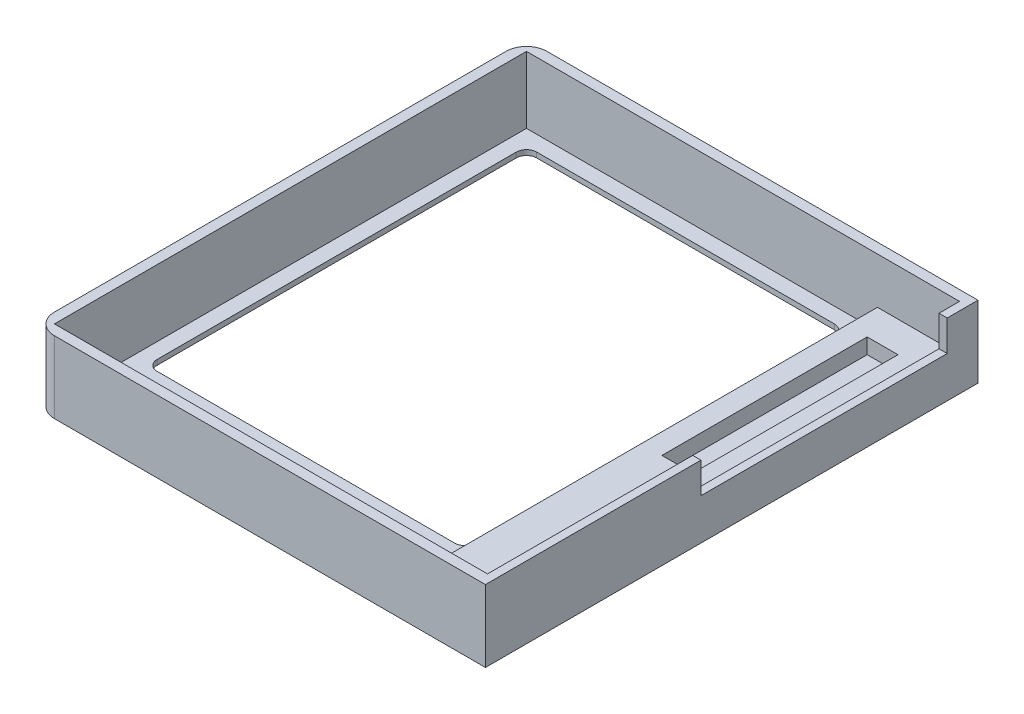
SolidWorks part; units mm, degrees
ref_plane "Front Plane" through (0, 0, 0) normal (0, 0, 1) x (1, 0, 0)
ref_plane "Top Plane" through (0, 0, 0) normal (0, 1, 0) x (1, 0, 0)
ref_plane "Right Plane" through (0, 0, 0) normal (1, 0, 0) x (0, 0, -1)
sketch "Sketch1" plane through (0, 0, 0) normal (0, 1, 0) x (1, 0, 0)
  line L1 (0, 0) -> (44, 0)
  line L2 (0, 0) -> (0, 48)
  line L3 (0, 48) -> (44, 48)
  line L4 (44, 0) -> (44, 48)
  dimension "D1" = 44
  dimension "D2" = 48
extrude "Boss-Extrude1" add sketch "Sketch1" along normal blind 7
sketch "Sketch2" plane through (0, 7, 0) normal (0, 1, 0) x (1, 0, 0)
  line L0 (44, 48) -> (0, 48) construction
  line L1 (1, 47) -> (43.2, 47)
  line L2 (1, 47) -> (1, 1)
  line L3 (1, 1) -> (43.2, 1)
  line L4 (43.2, 47) -> (43.2, 1)
  line L5 (0, 0) -> (44, 0) construction
  line L6 (0, 48) -> (0, 0) construction
  dimension "D1" = 1
  dimension "D2" = 1
  dimension "D3" = 1
  dimension "D4" = 42.2
extrude "Cut-Extrude1" cut sketch "Sketch2" against normal blind 6.5
sketch "Sketch3" plane through (0, 0.5, 0) normal (0, 1, 0) x (1, 0, 0)
  line L0 (1, 47) -> (1, 1) construction
  line L1 (2.5, 45.5) -> (33.5, 45.5)
  line L2 (2.5, 45.5) -> (2.5, 8.5)
  line L3 (2.5, 8.5) -> (33.5, 8.5)
  line L4 (33.5, 45.5) -> (33.5, 8.5)
  line L5 (43.2, 47) -> (1, 47) construction
  line L6 (1, 1) -> (43.2, 1) construction
  dimension "D1" = 1.5
  dimension "D2" = 1.5
  dimension "D3" = 7.5
  dimension "D4" = 31
extrude "Cut-Extrude2" cut sketch "Sketch3" against normal up to next
sketch "Sketch4" plane through (0, 0.5, 0) normal (0, 1, 0) x (1, 0, 0)
  line L0 (43.2, 47) -> (1, 47) construction
  line L1 (35.2, 47) -> (43.2, 47)
  line L2 (35.2, 47) -> (35.2, 1)
  line L3 (35.2, 1) -> (43.2, 1)
  line L4 (43.2, 47) -> (43.2, 1)
  dimension "D1" = 8
extrude "Boss-Extrude2" add sketch "Sketch4" along normal blind 2
sketch "Sketch5" plane through (0, 7, 0) normal (0, 1, 0) x (1, 0, 0)
  line L0 (43.2, 1) -> (43.2, 47) construction
  line L1 (43.2, 45) -> (44, 45)
  line L2 (43.2, 45) -> (43.2, 21)
  line L3 (43.2, 21) -> (44, 21)
  line L4 (44, 45) -> (44, 21)
  line L5 (44, 0) -> (44, 48) construction
  line L6 (43.2, 47) -> (1, 47) construction
  line L7 (35.2, 1) -> (43.2, 1) construction
  dimension "D1" = 2
  dimension "D2" = 20
extrude "Cut-Extrude3" cut sketch "Sketch5" against normal blind 3
fillet "Fillet1" radius 2 2 edges at (0, 3.5, -48) (0, 3.5, 0)
fillet "Fillet2" radius 1 4 edges at (33.5, 0.25, -45.5) (33.5, 0.25, -8.5) (2.5, 0.25, -45.5) (2.5, 0.25, -8.5)
sketch "Sketch6" plane through (0, 2.5, 0) normal (0, 1, 0) x (1, 0, 0)
  line L0 (43.2, 47) -> (1, 47) construction
  line L1 (37.2, 44) -> (40.2, 44)
  line L2 (37.2, 44) -> (37.2, 24)
  line L3 (37.2, 24) -> (40.2, 24)
  line L4 (40.2, 44) -> (40.2, 24)
  line L5 (43.2, 1) -> (43.2, 47) construction
  dimension "D1" = 3
  dimension "D2" = 23
  dimension "D3" = 3
  dimension "D4" = 3
extrude "Cut-Extrude4" cut sketch "Sketch6" against normal blind 1.5
